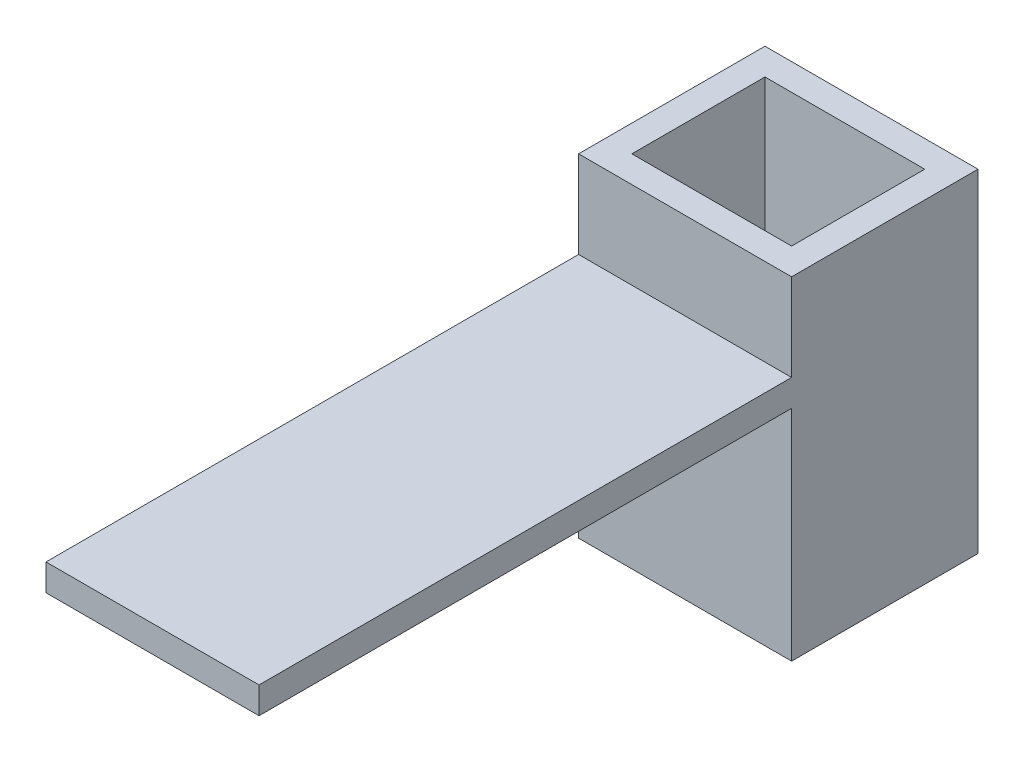
SolidWorks part; units mm, degrees
ref_plane "前视基准面" through (0, 0, 0) normal (0, 0, 1) x (1, 0, 0)
ref_plane "上视基准面" through (0, 0, 0) normal (0, 1, 0) x (1, 0, 0)
ref_plane "右视基准面" through (0, 0, 0) normal (1, 0, 0) x (0, 0, -1)
other "Configuration Table"
sketch "草图1" plane through (0, 0, 0) normal (0, 1, 0) x (1, 0, 0)
  line L1 (0, 0) -> (12, 0)
  line L2 (0, 0) -> (0, -10)
  line L3 (0, -10) -> (12, -10)
  line L4 (12, 0) -> (12, -10)
extrude "凸台-拉伸1" add sketch "草图1" along normal blind 25
shell "抽壳1" thickness 2
sketch "草图2" plane through (0, 0, 12) normal (0, 0, 1) x (1, 0, 0)
  line L0 (-2, 25) -> (-2, 0) construction
  line L1 (-2, 18.4544) -> (14, 18.4544)
  line L2 (-2, 18.4544) -> (-2, 16.4469)
  line L3 (-2, 16.4469) -> (14, 16.4469)
  line L4 (14, 18.4544) -> (14, 16.4469)
  line L5 (14, 25) -> (14, 0) construction
extrude "凸台-拉伸2" add sketch "草图2" along normal blind 40
